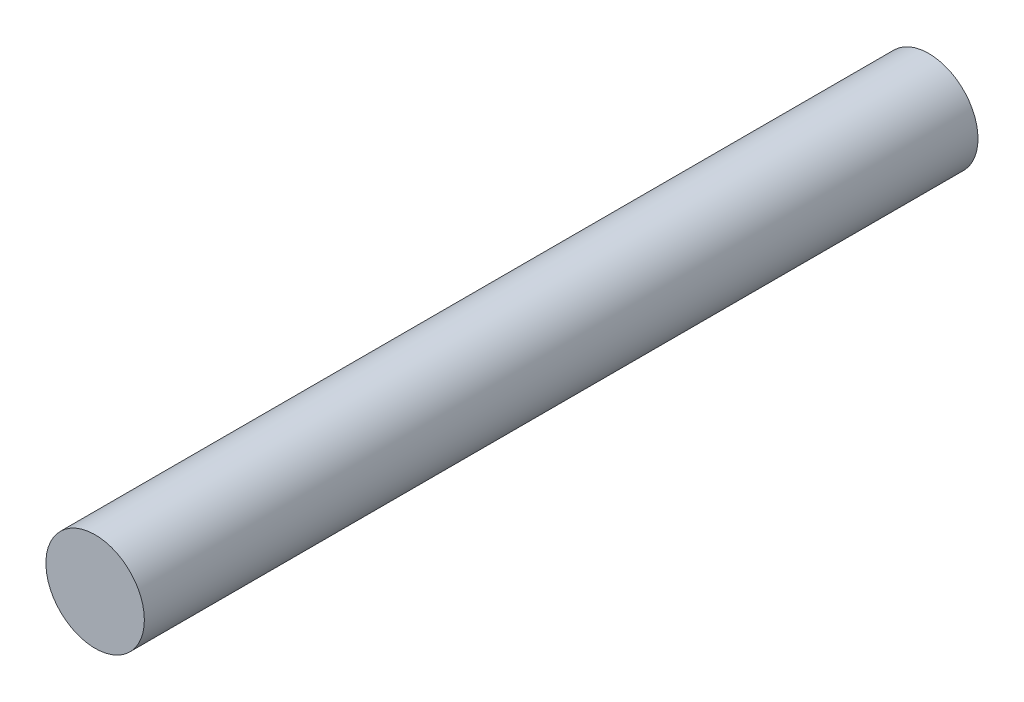
SolidWorks part; units mm, degrees
material "Brass"
ref_plane "Front Plane" through (0, 0, 0) normal (0, 0, 1) x (1, 0, 0)
ref_plane "Top Plane" through (0, 0, 0) normal (0, 1, 0) x (1, 0, 0)
ref_plane "Right Plane" through (0, 0, 0) normal (1, 0, 0) x (0, 0, -1)
sketch "Sketch1" plane through (0, 0, 0) normal (0, 0, 1) x (1, 0, 0)
  circle A0 centre (0, 0) radius 3
  dimension "D1" = 6
extrude "Boss-Extrude1" add sketch "Sketch1" along normal blind 50.8
